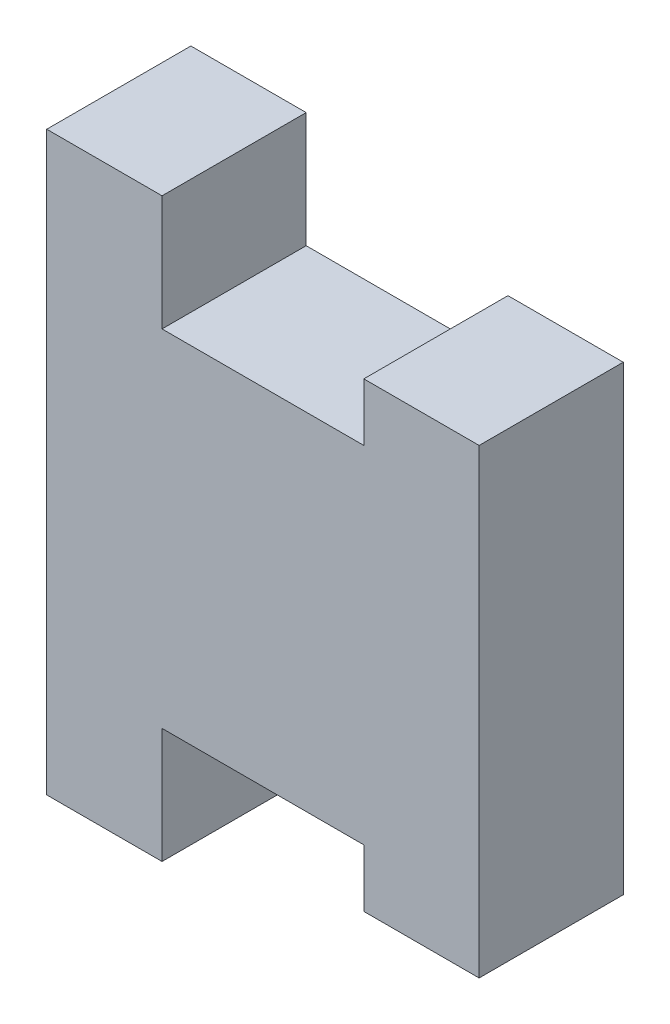
SolidWorks part; units mm, degrees
material "PBT General Purpose"
ref_plane "Front Plane" through (0, 0, 0) normal (0, 0, 1) x (1, 0, 0)
ref_plane "Top Plane" through (0, 0, 0) normal (0, 1, 0) x (1, 0, 0)
ref_plane "Right Plane" through (0, 0, 0) normal (1, 0, 0) x (0, 0, -1)
sketch "frame_outline" plane through (0, 0, 0) normal (0, 0, 1) x (1, 0, 0)
  line L110 (0, 0) -> (0, 1)
  line L111 (0, 1) -> (0.2, 1)
  line L112 (0.2, 1) -> (0.2, 0.8)
  line L113 (0.2, 0.8) -> (0.55, 0.8)
  line L114 (0.55, 0.8) -> (0.55, 0.9)
  line L115 (0.55, 0.9) -> (0.75, 0.9)
  line L116 (0.75, 0.9) -> (0.75, 0.1)
  line L117 (0.75, 0.1) -> (0.55, 0.1)
  line L118 (0.55, 0.1) -> (0.55, 0.2)
  line L119 (0.55, 0.2) -> (0.2, 0.2)
  line L120 (0.2, 0.2) -> (0.2, 0)
  line L121 (0.2, 0) -> (0, 0)
  line L122 (0.75, 0.5) -> (0, 0.5) construction
  line L123 (0.55, 0.8) -> (0.55, 0.2) construction
  point P11 (0.55, 0.5)
  dimension "D1" = 1
  dimension "D2" = 0.2
  dimension "D3" = 0.35
  dimension "D4" = 0.2
  dimension "D5" = 0.6
  dimension "D6" = 0.8
extrude "Boss-Extrude1" add sketch "frame_outline" along normal mid plane 0.25
equation "\"t\"= 0.25'thickness of the sheets"
equation "\"t_cf\" = 0.115'thickness of single carbon fiber layer"
equation "\"t_kapton\" = 0.025'thickness of single Kapton flex layer"
equation "\"t_fr4\" = 0.1'thickness of FR4 with copper layer"
equation "\"joint_flex\"= 0.1'Width of flextures gap"
equation "\"joint_flex_eff\"= 0.02'Width of flecture after castelation"
equation "\"joint_fold\"= 0.2'Width of folding joints for 90deg fold"
equation "\"gap_tolerance\"= 0.002'Width to have interfecence fit between carbon fiber inserts"
equation "\"assemble_angle\"= 90'Angle of assembly parts"
equation "\"D1@Boss-Extrude1\"=\"t\""
equation "\"link_lift\"= 0.5'Actuation linkage amplification for the lift motion"
equation "\"link_swing\"= 0.45'Actuation linkage amplification for the swing motion"
